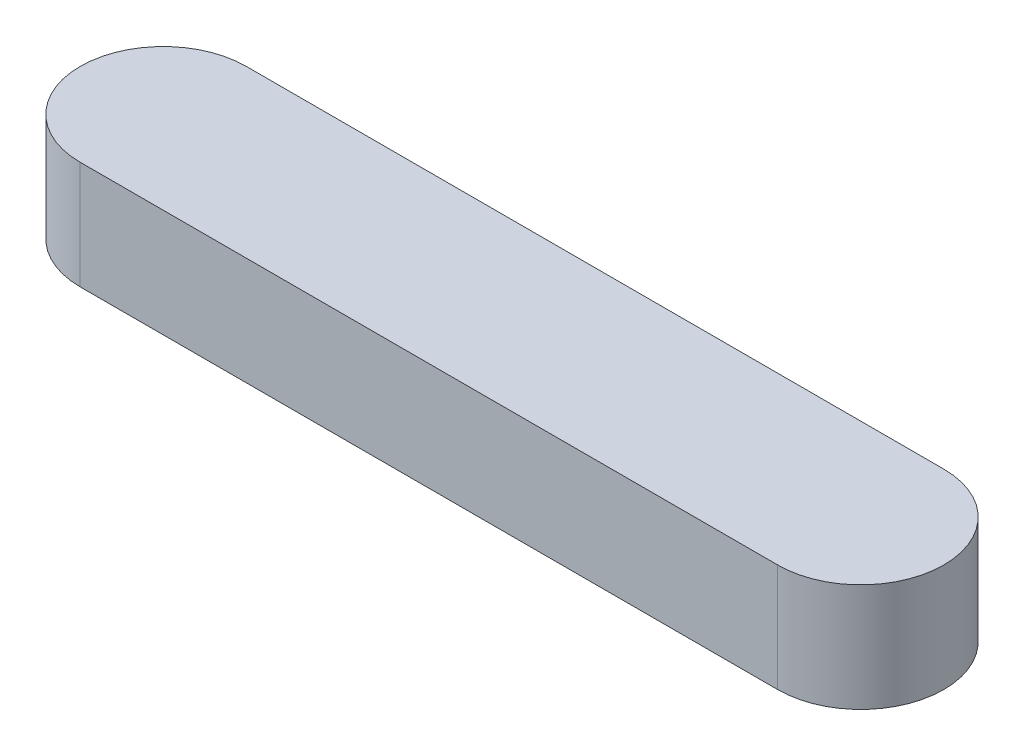
SolidWorks part; units mm, degrees
ref_plane "Front" through (0, 0, 0) normal (0, 0, 1) x (1, 0, 0)
ref_plane "Top" through (0, 0, 0) normal (0, 1, 0) x (1, 0, 0)
ref_plane "Right" through (0, 0, 0) normal (1, 0, 0) x (0, 0, -1)
other "Configuration Table"
sketch "Sketch1" plane through (0, 0, 0) normal (0, 1, 0) x (1, 0, 0)
  line L0 (0, 57.9521) -> (0, -57.6996) construction
  line L1 (-21, 0) -> (21, 0) construction
  line L2 (-21, 5) -> (21, 5)
  line L3 (-21, -5) -> (21, -5)
  arc A0 (-21, 5) -> (-21, -5) centre (-21, 0) ccw
  arc A1 (21, -5) -> (21, 5) centre (21, 0) ccw
  point P5 (0, 0)
  point P10 (-26, 0)
  point P11 (26, 0)
  dimension "D3" = 5
  dimension "D1" = 10
  dimension "D2" = 52
extrude "Boss-Extrude1" add sketch "Sketch1" along normal blind 6.5
